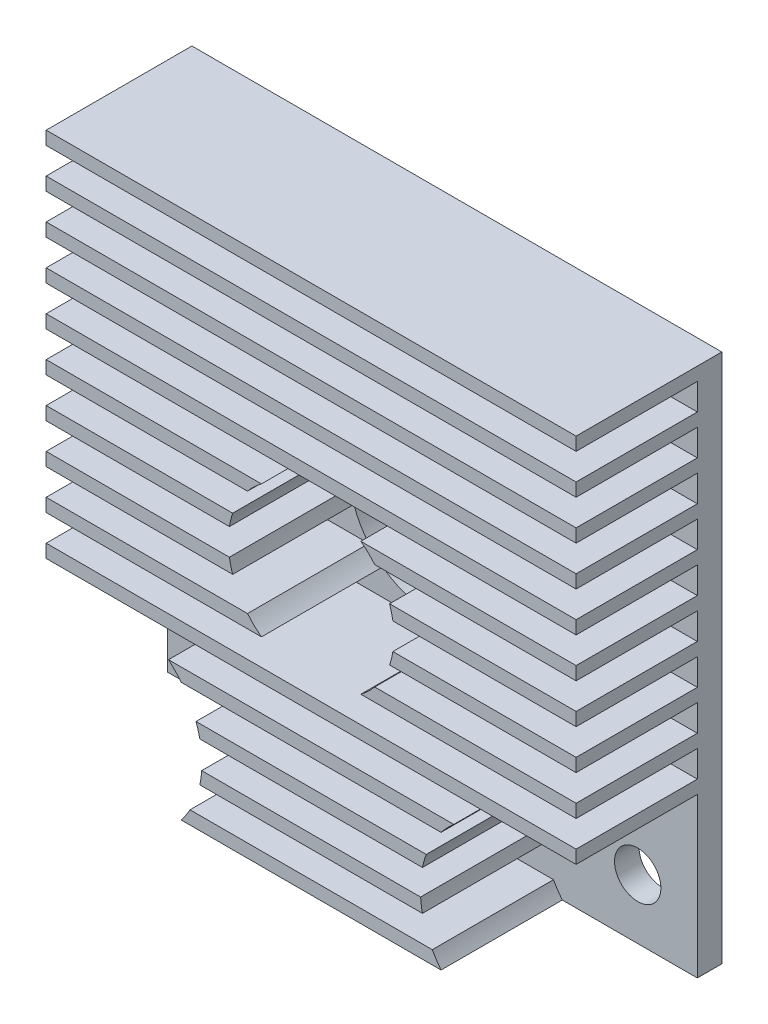
SolidWorks part; units mm, degrees
ref_plane "前视基准面" through (0, 0, 0) normal (0, 0, 1) x (1, 0, 0)
ref_plane "上视基准面" through (0, 0, 0) normal (0, 1, 0) x (1, 0, 0)
ref_plane "右视基准面" through (0, 0, 0) normal (1, 0, 0) x (0, 0, -1)
sketch "草图1" plane through (0, 0, 0) normal (0, 0, 1) x (1, 0, 0)
  line L1 (-20, 20) -> (20, 20)
  line L2 (-20, 20) -> (-20, -20)
  line L3 (-20, -20) -> (20, -20)
  line L4 (20, 20) -> (20, -20)
  line L5 (0, -20) -> (0, 20) construction
  line L6 (-20, 0) -> (20, 0) construction
  circle A0 centre (0, 0) radius 6.25
  point P0 (0, 0)
  dimension "D3" = 12.5
  dimension "D1" = 40
  dimension "D2" = 40
extrude "凸台-拉伸1" add sketch "草图1" along normal blind 1.85
sketch "草图2" plane through (0, 0, 1.85) normal (0, 0, 1) x (1, 0, 0)
  line L0 (20, -20) -> (20, 20) construction
  line L1 (-20, 20) -> (20, 20)
  line L2 (-20, 20) -> (-20, 19)
  line L3 (-20, 19) -> (20, 19)
  line L4 (20, 20) -> (20, 19)
  line L5 (-20, 20) -> (20, 19) construction
  line L6 (-20, 19) -> (20, 20) construction
  line L7 (-20, 17) -> (20, 17)
  line L8 (-20, 17) -> (-20, 16)
  line L9 (-20, 16) -> (20, 16)
  line L10 (20, 17) -> (20, 16)
  line L11 (-20, 17) -> (20, 16) construction
  line L12 (-20, 16) -> (20, 17) construction
  line L13 (-20, 14) -> (20, 14)
  line L14 (-20, 14) -> (-20, 13)
  line L15 (-20, 13) -> (20, 13)
  line L16 (20, 14) -> (20, 13)
  line L17 (-20, 14) -> (20, 13) construction
  line L18 (-20, 13) -> (20, 14) construction
  line L19 (-20, 11) -> (20, 11)
  line L20 (-20, 11) -> (-20, 10)
  line L21 (-20, 10) -> (20, 10)
  line L22 (20, 11) -> (20, 10)
  line L23 (-20, 11) -> (20, 10) construction
  line L24 (-20, 10) -> (20, 11) construction
  line L25 (-20, 8) -> (20, 8)
  line L26 (-20, 8) -> (-20, 7)
  line L27 (-20, 7) -> (20, 7)
  line L28 (20, 8) -> (20, 7)
  line L29 (-20, 8) -> (20, 7) construction
  line L30 (-20, 7) -> (20, 8) construction
  line L31 (-20, 5) -> (20, 5)
  line L32 (-20, 5) -> (-20, 4)
  line L33 (-20, 4) -> (20, 4)
  line L34 (20, 5) -> (20, 4)
  line L35 (-20, 5) -> (20, 4) construction
  line L36 (-20, 4) -> (20, 5) construction
  line L37 (-20, 2) -> (20, 2)
  line L38 (-20, 2) -> (-20, 1)
  line L39 (-20, 1) -> (20, 1)
  line L40 (20, 2) -> (20, 1)
  line L41 (-20, 2) -> (20, 1) construction
  line L42 (-20, 1) -> (20, 2) construction
  line L43 (-20, -1) -> (20, -1)
  line L44 (-20, -1) -> (-20, -2)
  line L45 (-20, -2) -> (20, -2)
  line L46 (20, -1) -> (20, -2)
  line L47 (-20, -1) -> (20, -2) construction
  line L48 (-20, -2) -> (20, -1) construction
  line L49 (-20, -4) -> (20, -4)
  line L50 (-20, -4) -> (-20, -5)
  line L51 (-20, -5) -> (20, -5)
  line L52 (20, -4) -> (20, -5)
  line L53 (-20, -4) -> (20, -5) construction
  line L54 (-20, -5) -> (20, -4) construction
  line L55 (-20, -7) -> (20, -7)
  line L56 (-20, -7) -> (-20, -8)
  line L57 (-20, -8) -> (20, -8)
  line L58 (20, -7) -> (20, -8)
  line L59 (-20, -7) -> (20, -8) construction
  line L60 (-20, -8) -> (20, -7) construction
  line L61 (-20, -10) -> (20, -10)
  line L62 (-20, -10) -> (-20, -11)
  line L63 (-20, -11) -> (20, -11)
  line L64 (20, -10) -> (20, -11)
  line L65 (-20, -10) -> (20, -11) construction
  line L66 (-20, -11) -> (20, -10) construction
  line L67 (-20, -13) -> (20, -13)
  line L68 (-20, -13) -> (-20, -14)
  line L69 (-20, -14) -> (20, -14)
  line L70 (20, -13) -> (20, -14)
  line L71 (-20, -13) -> (20, -14) construction
  line L72 (-20, -14) -> (20, -13) construction
  line L73 (-20, -16) -> (20, -16)
  line L74 (-20, -16) -> (-20, -17)
  line L75 (-20, -17) -> (20, -17)
  line L76 (20, -16) -> (20, -17)
  line L77 (-20, -16) -> (20, -17) construction
  line L78 (-20, -17) -> (20, -16) construction
  line L79 (-20, -19) -> (20, -19)
  line L80 (-20, -19) -> (-20, -20)
  line L81 (-20, -20) -> (20, -20)
  line L82 (20, -19) -> (20, -20)
  line L83 (-20, -19) -> (20, -20) construction
  line L84 (-20, -20) -> (20, -19) construction
  point P4 (0, 19.5)
  point P12 (0, 16.5)
  point P17 (0, 13.5)
  point P22 (0, 10.5)
  point P27 (0, 7.5)
  point P32 (0, 4.5)
  point P37 (0, 1.5)
  point P42 (0, -1.5)
  point P47 (0, -4.5)
  point P52 (0, -7.5)
  point P57 (0, -10.5)
  point P62 (0, -13.5)
  point P67 (0, -16.5)
  point P72 (0, -19.5)
  dimension "D1" = 1
  dimension "D2" = 14
extrude "凸台-拉伸2" add sketch "草图2" along normal blind 9.15
sketch "草图3" plane through (0, 0, 0) normal (0, 0, -1) x (-1, 0, 0)
  line L0 (20, -20) -> (-20, -20) construction
  line L2 (-20, -20) -> (-20, 20) construction
  circle A0 centre (-15.5, -15.5) radius 1.75
  circle A1 centre (15.5, -15.5) radius 1.75
  circle A2 centre (0, 0) radius 6.25 construction
  circle A3 centre (0, 0) radius 6.25
  dimension "D1" = 3.5
  dimension "D2" = 3.5
  dimension "D3" = 31
  dimension "D4" = 4.5
  dimension "D5" = 4.5
  dimension "D6" = 4.5
extrude "切除-拉伸5" cut sketch "草图3" against normal through all
sketch "草图4" plane through (0, 0, 1.85) normal (0, 0, 1) x (1, 0, 0)
  circle A0 centre (-15.5, -15.5) radius 7.2557
  circle A1 centre (15.5, -15.5) radius 7.2557
extrude "切除-拉伸6" cut sketch "草图4" along normal blind 16.15
